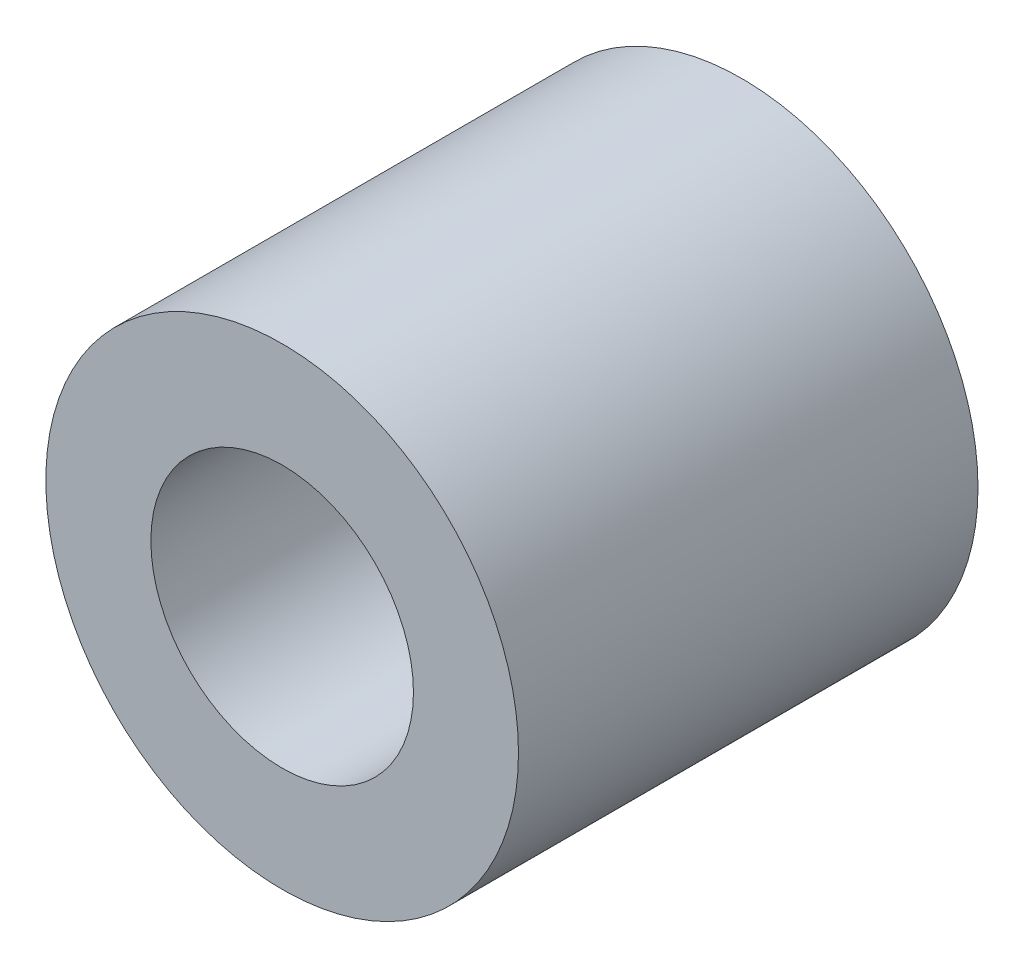
SolidWorks part; units mm, degrees
ref_plane "Plan de face" through (0, 0, 0) normal (0, 0, 1) x (1, 0, 0)
ref_plane "Plan de dessus" through (0, 0, 0) normal (0, 1, 0) x (1, 0, 0)
ref_plane "Plan de droite" through (0, 0, 0) normal (1, 0, 0) x (0, 0, -1)
sketch "Esquisse1" plane through (0, 0, 0) normal (0, 0, 1) x (1, 0, 0)
  circle A0 centre (0, 0) radius 9
  circle A1 centre (0, 0) radius 5
  dimension "D1" = 18
  dimension "D2" = 10
extrude "Boss.-Extru.1" add sketch "Esquisse1" along normal blind 17.5
